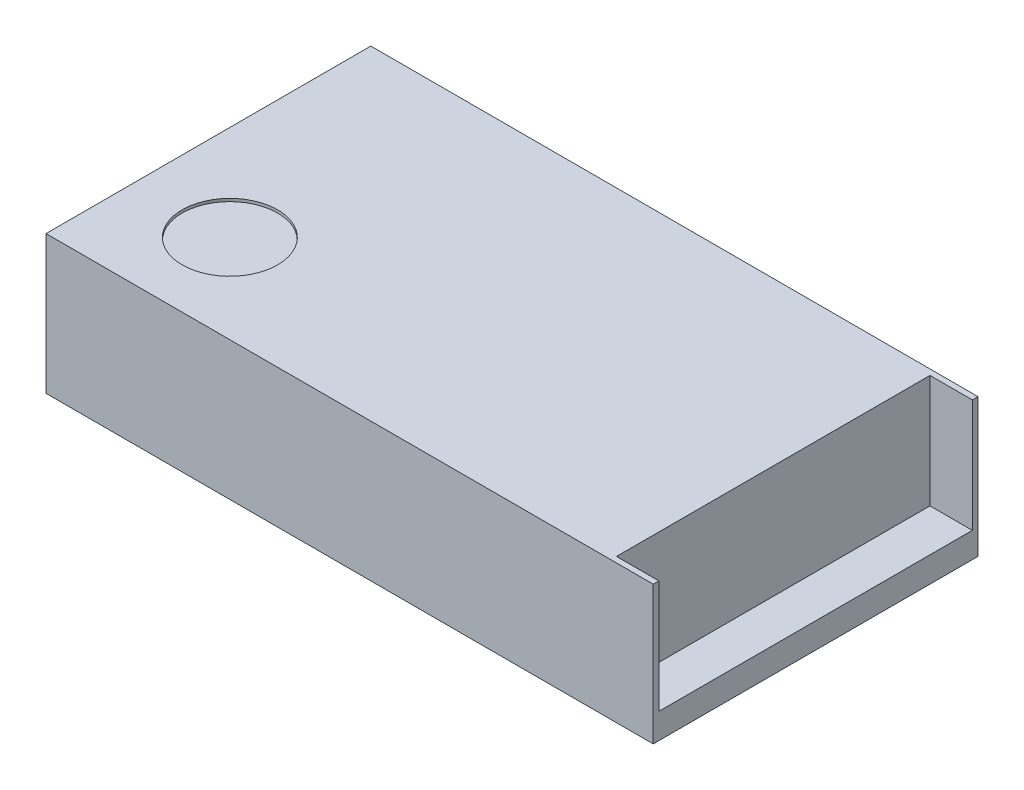
SolidWorks part; units mm, degrees
ref_plane "Front Plane" through (0, 0, 0) normal (0, 0, 1) x (1, 0, 0)
ref_plane "Top Plane" through (0, 0, 0) normal (0, 1, 0) x (1, 0, 0)
ref_plane "Right Plane" through (0, 0, 0) normal (1, 0, 0) x (0, 0, -1)
sketch "Sketch1" plane through (0, 0, 0) normal (0, 1, 0) x (1, 0, 0)
  line L1 (-107.5, -57.5) -> (107.5, -57.5)
  line L2 (-107.5, -57.5) -> (-107.5, 57.5)
  line L3 (-107.5, 57.5) -> (107.5, 57.5)
  line L4 (107.5, -57.5) -> (107.5, 57.5)
  line L5 (-107.5, -57.5) -> (107.5, 57.5) construction
  line L6 (-107.5, 57.5) -> (107.5, -57.5) construction
  point P0 (0, 0)
  dimension "D1" = 215
  dimension "D2" = 115
extrude "Boss-Extrude1" add sketch "Sketch1" along normal blind 49
sketch "Sketch2" plane through (0, 49, 0) normal (0, 1, 0) x (1, 0, 0)
  circle A0 centre (-73.7948, -26.1004) radius 16.8996
extrude "Cut-Extrude1" cut sketch "Sketch2" against normal blind 1
sketch "Sketch4" plane through (0, 49, 0) normal (0, 1, 0) x (1, 0, 0)
  line L0 (107.5, -57.5) -> (107.5, 57.5) construction
  line L1 (107.5, 55.5) -> (92.5, 55.5)
  line L2 (107.5, 55.5) -> (107.5, -55.5)
  line L3 (107.5, -55.5) -> (92.5, -55.5)
  line L4 (92.5, 55.5) -> (92.5, -55.5)
  line L5 (107.5, 57.5) -> (-107.5, 57.5) construction
  line L6 (-107.5, -57.5) -> (107.5, -57.5) construction
  dimension "D1" = 2
  dimension "D2" = 2
  dimension "D3" = 15
extrude "Cut-Extrude2" cut sketch "Sketch4" against normal blind 40
equation "\"D2@Sketch4\"=\"D1@Sketch4\""
